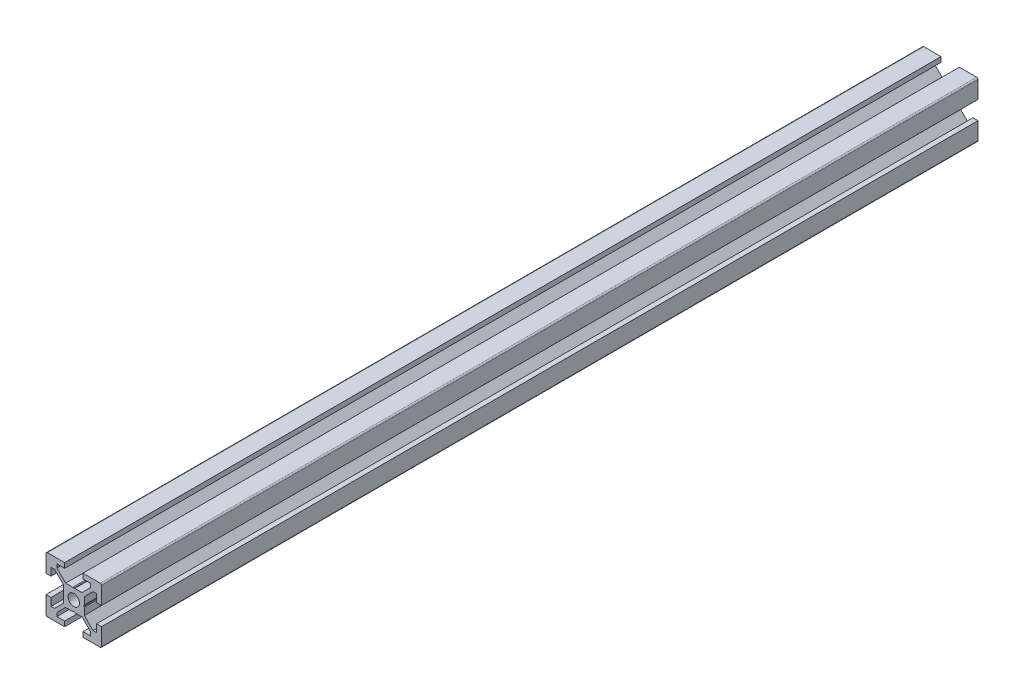
SolidWorks part; units mm, degrees
ref_plane "Front Plane" through (0, 0, 0) normal (0, 0, 1) x (1, 0, 0)
ref_plane "Top Plane" through (0, 0, 0) normal (0, 1, 0) x (1, 0, 0)
ref_plane "Right Plane" through (0, 0, 0) normal (1, 0, 0) x (0, 0, -1)
sketch "Sketch1" plane through (0, 0, 0) normal (0, 0, 1) x (1, 0, 0)
  line L0 (-3.3, 10) -> (-3.3, 8.2)
  line L1 (0, 0) -> (50000, 0) construction
  line L2 (-10, 3.3) -> (-10, 10)
  line L3 (-10, 10) -> (-3.3, 10)
  line L4 (0, 0) -> (0, 50000) construction
  line L5 (-10, -10) -> (10, 10) construction
  line L6 (-10, 10) -> (10, -10) construction
  line L7 (-2.9315, -3.78) -> (-0.34, -3.78)
  line L8 (-3.78, -2.9315) -> (-3.78, -0.34)
  line L9 (-2.9315, 3.78) -> (-0.34, 3.78)
  line L10 (3.78, -2.9315) -> (3.78, -0.34)
  line L11 (-3.78, -3.78) -> (3.78, 3.78) construction
  line L12 (-3.78, 3.78) -> (3.78, -3.78) construction
  line L13 (-6.08, 8.2) -> (-3.3, 8.2)
  line L14 (-8.2, 6.08) -> (-8.2, 3.3)
  line L15 (-8.2, 3.3) -> (-10, 3.3)
  line L16 (-8.2, 6.08) -> (-6.9285, 6.08)
  line L17 (-6.08, 8.2) -> (-6.08, 6.9285)
  line L18 (-6.9285, 6.08) -> (-3.78, 2.9315)
  line L19 (-6.08, 6.9285) -> (-2.9315, 3.78)
  line L20 (8.2, 6.08) -> (6.9285, 6.08)
  line L21 (8.2, 6.08) -> (8.2, 3.3)
  line L22 (8.2, 3.3) -> (10, 3.3)
  line L23 (10, 3.3) -> (10, 10)
  line L24 (10, 10) -> (3.3, 10)
  line L25 (3.3, 10) -> (3.3, 8.2)
  line L26 (6.08, 8.2) -> (3.3, 8.2)
  line L27 (6.08, 8.2) -> (6.08, 6.9285)
  line L28 (6.08, 6.9285) -> (2.9315, 3.78)
  line L29 (6.9285, 6.08) -> (3.78, 2.9315)
  line L30 (6.9285, -6.08) -> (3.78, -2.9315)
  line L31 (6.08, -6.9285) -> (2.9315, -3.78)
  line L32 (6.08, -8.2) -> (6.08, -6.9285)
  line L33 (6.08, -8.2) -> (3.3, -8.2)
  line L34 (3.3, -10) -> (3.3, -8.2)
  line L35 (10, -10) -> (3.3, -10)
  line L36 (10, -3.3) -> (10, -10)
  line L37 (8.2, -3.3) -> (10, -3.3)
  line L38 (8.2, -6.08) -> (8.2, -3.3)
  line L39 (8.2, -6.08) -> (6.9285, -6.08)
  line L40 (-6.08, -6.9285) -> (-2.9315, -3.78)
  line L41 (-6.9285, -6.08) -> (-3.78, -2.9315)
  line L42 (-6.08, -8.2) -> (-6.08, -6.9285)
  line L43 (-8.2, -6.08) -> (-6.9285, -6.08)
  line L44 (-8.2, -3.3) -> (-10, -3.3)
  line L45 (-8.2, -6.08) -> (-8.2, -3.3)
  line L46 (-6.08, -8.2) -> (-3.3, -8.2)
  line L47 (-10, -10) -> (-3.3, -10)
  line L48 (-10, -3.3) -> (-10, -10)
  line L49 (-3.3, -10) -> (-3.3, -8.2)
  line L50 (-0.34, 3.78) -> (0, 3.66)
  line L51 (0.34, 3.78) -> (0, 3.66)
  line L52 (0.34, 3.78) -> (2.9315, 3.78)
  line L53 (-3.78, -0.34) -> (-3.66, 0)
  line L54 (-3.78, 0.34) -> (-3.66, 0)
  line L55 (3.78, 0.34) -> (3.66, 0)
  line L56 (3.78, -0.34) -> (3.66, 0)
  line L57 (-0.34, -3.78) -> (0, -3.66)
  line L58 (0.34, -3.78) -> (0, -3.66)
  line L59 (3.78, 0.34) -> (3.78, 2.9315)
  line L60 (0.34, -3.78) -> (2.9315, -3.78)
  line L61 (-3.78, 0.34) -> (-3.78, 2.9315)
  circle A0 centre (0, 0) radius 2.05
  point P0 (0, 0)
  dimension "D3" = 4.1
  dimension "D1" = 20
  dimension "D2" = 20
  dimension "D4" = 7.56
  dimension "D5" = 6.7
  dimension "D6" = 6.7
  dimension "D7" = 0.6
  dimension "D8" = 3.92
  dimension "D9" = 0.34
  dimension "D10" = 0.12
extrude "Boss-Extrude1" add sketch "Sketch1" along normal blind 315.25
fillet "Fillet1" radius 0.5 4 edges at (-10, 10, 157.625) (-10, -10, 157.625) (10, -10, 157.625) (10, 10, 157.625)
